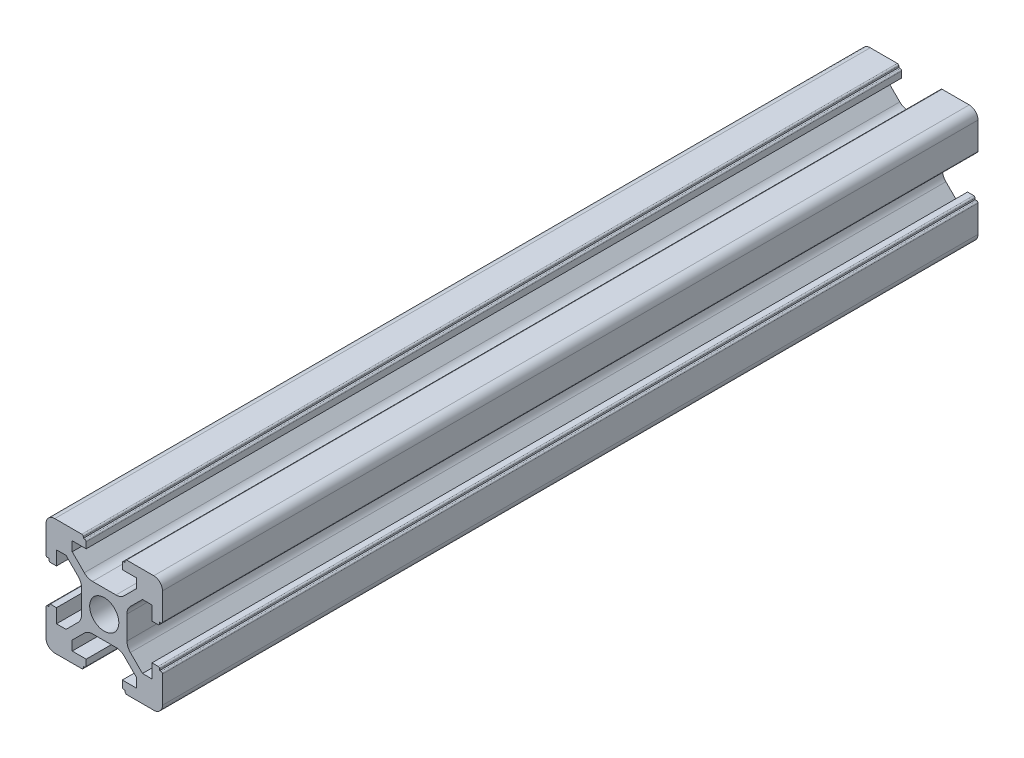
SolidWorks part; units mm, degrees
ref_plane "Front Plane" through (0, 0, 0) normal (0, 0, 1) x (1, 0, 0)
ref_plane "Top Plane" through (0, 0, 0) normal (0, 1, 0) x (1, 0, 0)
ref_plane "Right Plane" through (0, 0, 0) normal (1, 0, 0) x (0, 0, -1)
sketch "Sketch1" plane through (0, 0, 0) normal (0, 0, 1) x (1, 0, 0)
  line L0 (0, 0) -> (-10, 10) construction
  line L5 (0, 0) -> (10, 10) construction
  line L6 (22.7721, 0) -> (-22.7721, 0) construction
  line L7 (-8.5, 10) -> (-3.85, 10)
  line L8 (8.5, 10) -> (3.85, 10)
  line L9 (-3.6, 9.75) -> (-3.6, 9.5)
  line L10 (-3.6, 9.5) -> (-3.35, 9.5)
  line L11 (3.6, 9.75) -> (3.6, 9.5)
  line L12 (3.6, 9.5) -> (3.35, 9.5)
  line L13 (-3.1, 9.25) -> (-3.1, 8.2)
  line L14 (3.1, 9.25) -> (3.1, 8.2)
  line L15 (-3.1, 8.2) -> (-5.5, 8.2)
  line L16 (3.1, 8.2) -> (5.5, 8.2)
  line L17 (-3.4251, 4.4858) -> (-5.5, 6.5607)
  line L18 (-2.0109, 3.9) -> (2.0109, 3.9)
  line L19 (-5.5, 6.5607) -> (-5.5, 8.2)
  line L20 (5.5, 6.5607) -> (3.4251, 4.4858)
  line L21 (5.5, 6.5607) -> (5.5, 8.2)
  line L22 (10, 8.5) -> (10, 3.85)
  line L23 (10, -8.5) -> (10, -3.85)
  line L24 (9.75, 3.6) -> (9.5, 3.6)
  line L25 (9.5, 3.6) -> (9.5, 3.35)
  line L26 (9.75, -3.6) -> (9.5, -3.6)
  line L27 (9.5, -3.6) -> (9.5, -3.35)
  line L28 (9.25, 3.1) -> (8.2, 3.1)
  line L29 (9.25, -3.1) -> (8.2, -3.1)
  line L30 (8.2, 3.1) -> (8.2, 5.5)
  line L31 (8.2, -3.1) -> (8.2, -5.5)
  line L32 (4.4858, 3.4251) -> (6.5607, 5.5)
  line L33 (3.9, 2.0109) -> (3.9, -2.0109)
  line L34 (6.5607, 5.5) -> (8.2, 5.5)
  line L35 (6.5607, -5.5) -> (4.4858, -3.4251)
  line L36 (6.5607, -5.5) -> (8.2, -5.5)
  line L37 (8.5, -10) -> (3.85, -10)
  line L38 (-8.5, -10) -> (-3.85, -10)
  line L39 (3.6, -9.75) -> (3.6, -9.5)
  line L40 (3.6, -9.5) -> (3.35, -9.5)
  line L41 (-3.6, -9.75) -> (-3.6, -9.5)
  line L42 (-3.6, -9.5) -> (-3.35, -9.5)
  line L43 (3.1, -9.25) -> (3.1, -8.2)
  line L44 (-3.1, -9.25) -> (-3.1, -8.2)
  line L45 (3.1, -8.2) -> (5.5, -8.2)
  line L46 (-3.1, -8.2) -> (-5.5, -8.2)
  line L47 (3.4251, -4.4858) -> (5.5, -6.5607)
  line L48 (2.0109, -3.9) -> (-2.0109, -3.9)
  line L49 (5.5, -6.5607) -> (5.5, -8.2)
  line L50 (-5.5, -6.5607) -> (-3.4251, -4.4858)
  line L51 (-5.5, -6.5607) -> (-5.5, -8.2)
  line L52 (-10, -8.5) -> (-10, -3.85)
  line L53 (-10, 8.5) -> (-10, 3.85)
  line L54 (-9.75, -3.6) -> (-9.5, -3.6)
  line L55 (-9.5, -3.6) -> (-9.5, -3.35)
  line L56 (-9.75, 3.6) -> (-9.5, 3.6)
  line L57 (-9.5, 3.6) -> (-9.5, 3.35)
  line L58 (-9.25, -3.1) -> (-8.2, -3.1)
  line L59 (-9.25, 3.1) -> (-8.2, 3.1)
  line L60 (-8.2, -3.1) -> (-8.2, -5.5)
  line L61 (-8.2, 3.1) -> (-8.2, 5.5)
  line L62 (-4.4858, -3.4251) -> (-6.5607, -5.5)
  line L63 (-3.9, -2.0109) -> (-3.9, 2.0109)
  line L64 (-6.5607, -5.5) -> (-8.2, -5.5)
  line L65 (-6.5607, 5.5) -> (-4.4858, 3.4251)
  line L66 (-6.5607, 5.5) -> (-8.2, 5.5)
  circle A5 centre (0, 0) radius 2.5
  arc A6 (-8.5, -10) -> (-10, -8.5) centre (-8.5, -8.5) cw
  arc A7 (10, -8.5) -> (8.5, -10) centre (8.5, -8.5) cw
  arc A8 (8.5, 10) -> (10, 8.5) centre (8.5, 8.5) cw
  arc A9 (-8.5, 10) -> (-10, 8.5) centre (-8.5, 8.5) ccw
  arc A10 (-4.4858, -3.4251) -> (-3.9, -2.0109) centre (-5.9, -2.0109) ccw
  arc A11 (-2.0109, -3.9) -> (-3.4251, -4.4858) centre (-2.0109, -5.9) ccw
  arc A12 (3.4251, -4.4858) -> (2.0109, -3.9) centre (2.0109, -5.9) ccw
  arc A13 (3.9, -2.0109) -> (4.4858, -3.4251) centre (5.9, -2.0109) ccw
  arc A14 (4.4858, 3.4251) -> (3.9, 2.0109) centre (5.9, 2.0109) ccw
  arc A15 (3.4251, 4.4858) -> (2.0109, 3.9) centre (2.0109, 5.9) cw
  arc A16 (-3.4251, 4.4858) -> (-2.0109, 3.9) centre (-2.0109, 5.9) ccw
  arc A17 (-3.9, 2.0109) -> (-4.4858, 3.4251) centre (-5.9, 2.0109) ccw
  arc A18 (10, 3.85) -> (9.75, 3.6) centre (9.75, 3.85) cw
  arc A19 (9.5, 3.35) -> (9.25, 3.1) centre (9.25, 3.35) cw
  arc A20 (10, -3.85) -> (9.75, -3.6) centre (9.75, -3.85) ccw
  arc A21 (9.5, -3.35) -> (9.25, -3.1) centre (9.25, -3.35) ccw
  arc A22 (3.85, -10) -> (3.6, -9.75) centre (3.85, -9.75) cw
  arc A23 (3.1, -9.25) -> (3.35, -9.5) centre (3.35, -9.25) ccw
  arc A24 (-3.1, -9.25) -> (-3.35, -9.5) centre (-3.35, -9.25) cw
  arc A25 (-3.85, -10) -> (-3.6, -9.75) centre (-3.85, -9.75) ccw
  arc A26 (-10, -3.85) -> (-9.75, -3.6) centre (-9.75, -3.85) cw
  arc A27 (-9.25, -3.1) -> (-9.5, -3.35) centre (-9.25, -3.35) ccw
  arc A28 (-9.5, 3.35) -> (-9.25, 3.1) centre (-9.25, 3.35) ccw
  arc A29 (-10, 3.85) -> (-9.75, 3.6) centre (-9.75, 3.85) ccw
  arc A30 (-3.1, 9.25) -> (-3.35, 9.5) centre (-3.35, 9.25) ccw
  arc A31 (-3.85, 10) -> (-3.6, 9.75) centre (-3.85, 9.75) cw
  arc A32 (3.35, 9.5) -> (3.1, 9.25) centre (3.35, 9.25) ccw
  arc A33 (3.85, 10) -> (3.6, 9.75) centre (3.85, 9.75) ccw
  point P6 (-3.1, 9.5)
  point P7 (0, 0)
  point P28 (9.5, 3.1)
  point P46 (3.1, -9.5)
  point P63 (-9.5, -3.1)
  point P77 (0, 0)
  point P123 (-3.1, 9.5)
  point P126 (-3.6, 10)
  point P129 (3.1, 9.5)
  point P132 (3.6, 10)
  dimension "D1" = 45
  dimension "D4" = 7.2
  dimension "D2" = 5
  dimension "D13" = 1.5
  dimension "D14" = 2
  dimension "D15" = 0.25
  dimension "D3" = 20
  dimension "D5" = 0.5
  dimension "D6" = 6.2
  dimension "D7" = 1.8
  dimension "D8" = 11
  dimension "D9" = 0.75
  dimension "D10" = 6.1
  dimension "D11" = 0.75
  dimension "D12" = 4
extrude "Boss-Extrude1" add sketch "Sketch1" along normal blind 140
